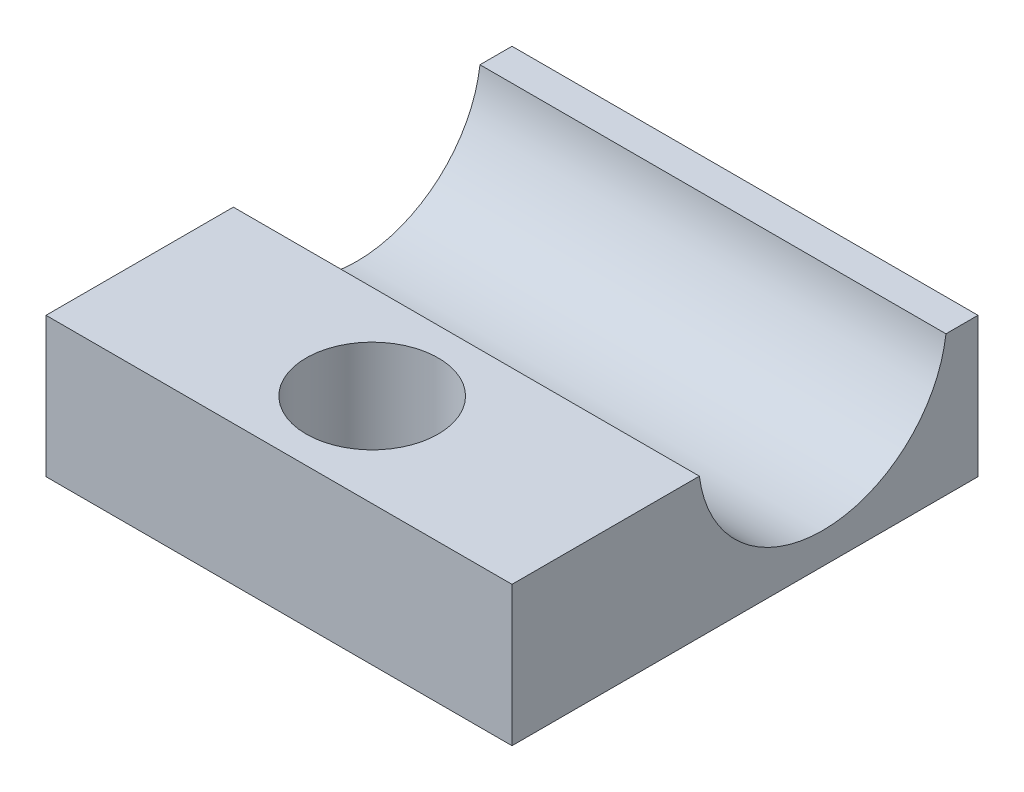
SolidWorks part; units mm, degrees
ref_plane "Front Plane" through (0, 0, 0) normal (0, 0, 1) x (1, 0, 0)
ref_plane "Top Plane" through (0, 0, 0) normal (0, 1, 0) x (1, 0, 0)
ref_plane "Right Plane" through (0, 0, 0) normal (1, 0, 0) x (0, 0, -1)
sketch "Sketch1" plane through (0, 0, 0) normal (0, 1, 0) x (1, 0, 0)
  line L1 (-15, 15) -> (0, 15)
  line L2 (-15, 15) -> (-15, 0)
  line L3 (-15, 0) -> (0, 0)
  line L4 (0, 15) -> (0, 0)
  circle A0 centre (-7.5, 3) radius 2.125
  dimension "D5" = 4.25
  dimension "D1" = 15
  dimension "D2" = 15
  dimension "D3" = 3
  dimension "D4" = 7.5
extrude "Boss-Extrude1" add sketch "Sketch1" along normal blind 4.5
sketch "Sketch2" plane through (0, 0, 0) normal (1, 0, 0) x (0, 0, -1)
  line L0 (15, 4.5) -> (15, 0) construction
  line L1 (0, 0) -> (15, 0) construction
  circle A0 centre (10, 5) radius 4
  dimension "D1" = 8
  dimension "D2" = 5
  dimension "D3" = 5
extrude "Cut-Extrude1" cut sketch "Sketch2" against normal up to next
